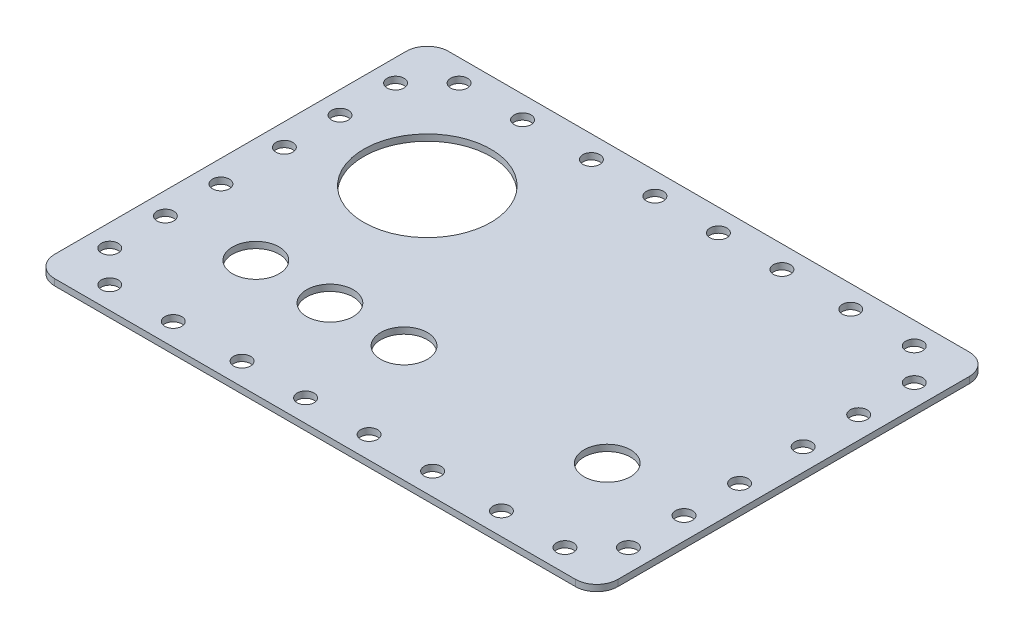
SolidWorks part; units mm, degrees
material "5052-H32"
ref_plane "Front Plane" through (0, 0, 0) normal (0, 0, 1) x (1, 0, 0)
ref_plane "Top Plane" through (0, 0, 0) normal (0, 1, 0) x (1, 0, 0)
ref_plane "Right Plane" through (0, 0, 0) normal (1, 0, 0) x (0, 0, -1)
sketch "Sketch1" plane through (0, 0, 0) normal (0, 1, 0) x (1, 0, 0)
  line L1 (-133, 93) -> (133, 93)
  line L2 (-133, 93) -> (-133, -93)
  line L3 (-133, -93) -> (133, -93)
  line L4 (133, 93) -> (133, -93)
  line L5 (-133, 93) -> (133, -93) construction
  line L6 (-133, -93) -> (133, 93) construction
  point P4 (0, 0)
  dimension "D1" = 266
  dimension "D2" = 186
extrude "Boss-Extrude1" add sketch "Sketch1" along normal blind 3
fillet "Fillet1" radius 10 4 edges at (-133, 1.5, -93) (133, 1.5, -93) (133, 1.5, 93) (-133, 1.5, 93)
sketch "Sketch2" plane through (0, 3, 0) normal (0, 1, 0) x (1, 0, 0)
  line L0 (123, 93) -> (-123, 93) construction
  line L1 (-122.5, 82.5) -> (122.5, 82.5) construction
  line L2 (-122.5, 82.5) -> (-122.5, -82.5) construction
  line L3 (-122.5, -82.5) -> (122.5, -82.5) construction
  line L4 (122.5, 82.5) -> (122.5, -82.5) construction
  line L5 (-122.5, 82.5) -> (122.5, -82.5) construction
  line L6 (-122.5, -82.5) -> (122.5, 82.5) construction
  line L7 (-133, 83) -> (-133, -83) construction
  line L8 (0, 82.5) -> (0, -82.5) construction
  line L9 (-122.5, 0) -> (122.5, 0) construction
  line L10 (-123, -93) -> (123, -93) construction
  line L11 (133, -83) -> (133, 83) construction
  circle A0 centre (-122.5, -15) radius 4
  circle A1 centre (-122.5, -41.25) radius 4
  circle A2 centre (-122.5, -67.5) radius 4
  circle A3 centre (-107.5, -82.5) radius 4
  circle A4 centre (-77.5, -82.5) radius 4
  circle A5 centre (-45, -82.5) radius 4
  circle A6 centre (-15, -82.5) radius 4
  circle A7 centre (-15, 82.5) radius 4
  circle A8 centre (-45, 82.5) radius 4
  circle A9 centre (-77.5, 82.5) radius 4
  circle A10 centre (-107.5, 82.5) radius 4
  circle A11 centre (-122.5, 67.5) radius 4
  circle A12 centre (-122.5, 41.25) radius 4
  circle A13 centre (-122.5, 15) radius 4
  circle A14 centre (15, -82.5) radius 4
  circle A16 centre (107.5, -82.5) radius 4
  circle A17 centre (122.5, -67.5) radius 4
  circle A18 centre (122.5, -41.25) radius 4
  circle A19 centre (122.5, -15) radius 4
  circle A20 centre (122.5, 15) radius 4
  circle A21 centre (122.5, 41.25) radius 4
  circle A22 centre (122.5, 67.5) radius 4
  circle A23 centre (107.5, 82.5) radius 4
  circle A24 centre (77.5, 82.5) radius 4
  circle A25 centre (45, 82.5) radius 4
  circle A26 centre (15, 82.5) radius 4
  circle A27 centre (-73, 33) radius 30
  circle A28 centre (83, -38) radius 11
  circle A29 centre (-83, -38) radius 11
  circle A30 centre (-48, -38) radius 11
  circle A31 centre (-13, -38) radius 11
  circle A32 centre (45, -82.5) radius 4
  circle A33 centre (77.5, -82.5) radius 4
  point P4 (0, 0)
  dimension "D3" = 8
  dimension "D11" = 60
  dimension "D14" = 22
  dimension "D1" = 10.5
  dimension "D2" = 10.5
  dimension "D4" = 15
  dimension "D5" = 15
  dimension "D6" = 45
  dimension "D7" = 45
  dimension "D8" = 15
  dimension "D9" = 15
  dimension "D10" = 41.25
  dimension "D12" = 60
  dimension "D13" = 60
  dimension "D15" = 55
  dimension "D16" = 50
  dimension "D17" = 50
  dimension "D18" = 35
  dimension "D19" = 35
extrude "Cut-Extrude1" cut sketch "Sketch2" against normal through all
